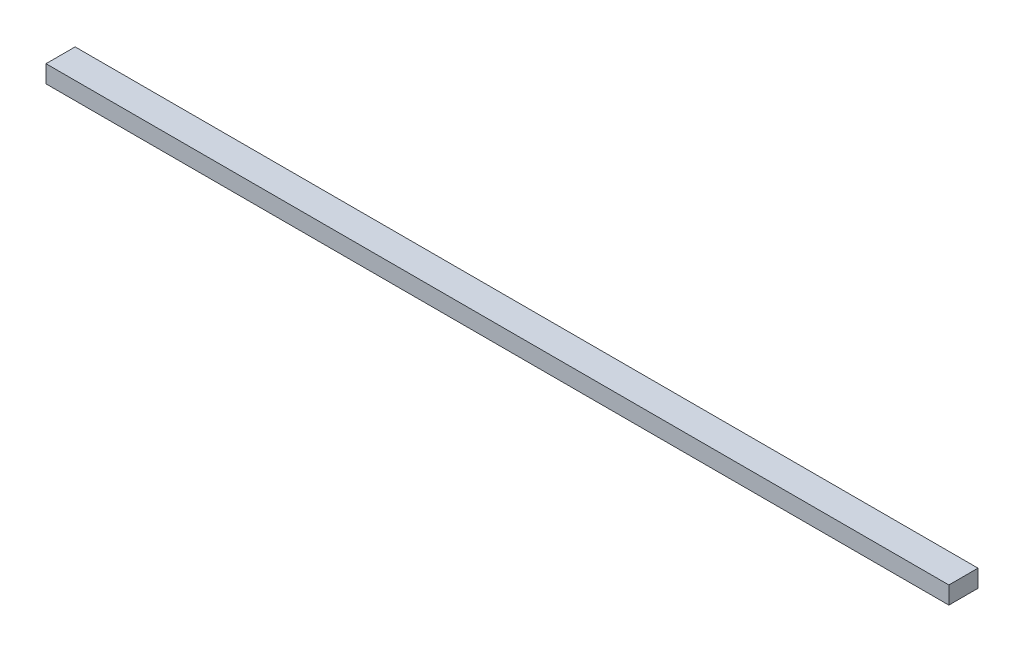
SolidWorks part; units mm, degrees
ref_plane "Front Plane" through (0, 0, 0) normal (0, 0, 1) x (1, 0, 0)
ref_plane "Top Plane" through (0, 0, 0) normal (0, 1, 0) x (1, 0, 0)
ref_plane "Right Plane" through (0, 0, 0) normal (1, 0, 0) x (0, 0, -1)
sketch "Sketch1" plane through (0, 0, 0) normal (0, 1, 0) x (1, 0, 0)
  line L1 (-77.5, -2.5) -> (77.5, -2.5)
  line L2 (-77.5, -2.5) -> (-77.5, 2.5)
  line L3 (-77.5, 2.5) -> (77.5, 2.5)
  line L4 (77.5, -2.5) -> (77.5, 2.5)
  line L5 (-77.5, -2.5) -> (77.5, 2.5) construction
  line L6 (-77.5, 2.5) -> (77.5, -2.5) construction
  point P0 (0, 0)
  dimension "D1" = 155
  dimension "D2" = 5
extrude "Boss-Extrude1" add sketch "Sketch1" along normal blind 3
